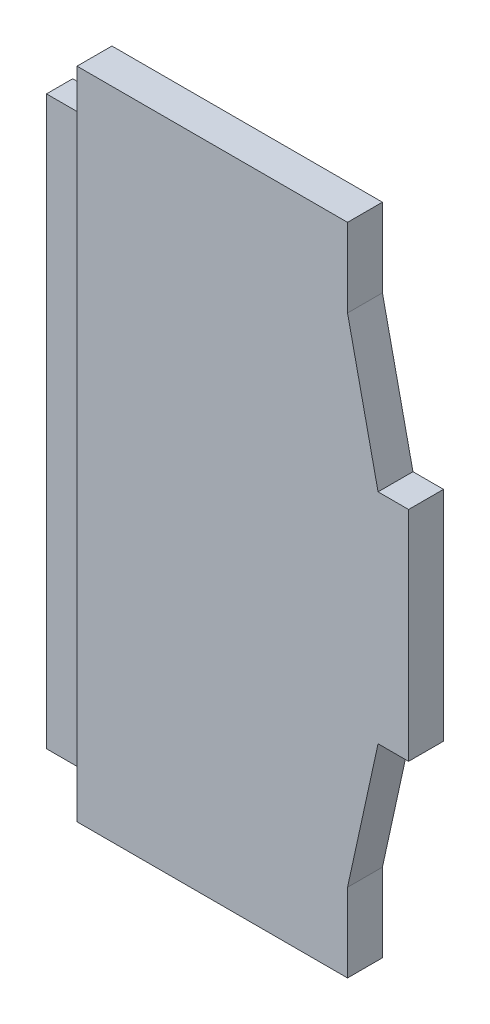
SolidWorks part; units mm, degrees
ref_plane "Front Plane" through (0, 0, 0) normal (0, 0, 1) x (1, 0, 0)
ref_plane "Top Plane" through (0, 0, 0) normal (0, 1, 0) x (1, 0, 0)
ref_plane "Right Plane" through (0, 0, 0) normal (1, 0, 0) x (0, 0, -1)
sketch "Sketch1" plane through (0, 0, 0) normal (0, 0, 1) x (1, 0, 0)
  line L0 (0, 37.5) -> (31, 37.5) construction
  line L1 (0, 0) -> (31, 0)
  line L2 (0, 0) -> (0, 75)
  line L3 (0, 75) -> (31, 75)
  line L4 (31, 0) -> (31, 9)
  line L5 (34.5, 50) -> (38, 50)
  line L6 (38, 50) -> (38, 25)
  line L7 (38, 25) -> (34.5, 25)
  line L8 (31, 66) -> (31, 75)
  line L9 (31, 50) -> (31, 37.5) construction
  line L10 (31, 37.5) -> (31, 25) construction
  line L11 (34.5, 50) -> (31, 66)
  line L12 (34.5, 25) -> (31, 9)
  line L13 (31, 25) -> (31, 9) construction
  line L14 (34.5, 25) -> (31, 25) construction
  line L15 (31, 50) -> (34.5, 50) construction
  line L16 (31, 50) -> (31, 66) construction
  line L17 (34, 45) -> (31, 45) construction
  line L18 (34, 45) -> (34, 50) construction
  circle A0 centre (34, 45) radius 1.55 construction
  circle A2 centre (34, 30) radius 1.55 construction
  dimension "D5" = 3.1
  dimension "D1" = 31
  dimension "D2" = 75
  dimension "D3" = 25
  dimension "D4" = 7
  dimension "D6" = 3
  dimension "D7" = 15
  dimension "D8" = 9
extrude "Boss-Extrude1" add sketch "Sketch1" along normal blind 4
sketch "Sketch3" plane through (0, 0, 0) normal (-1, 0, 0) x (0, 0, 1)
  line L0 (2, 0) -> (2, 75) construction
  line L1 (4, 0) -> (0, 0) construction
  line L2 (4, 75) -> (0, 75) construction
  line L3 (0, 37.5) -> (4, 37.5) construction
  line L4 (0.5, 70) -> (3.5, 70)
  line L5 (0.5, 70) -> (0.5, 5)
  line L6 (0.5, 5) -> (3.5, 5)
  line L7 (3.5, 70) -> (3.5, 5)
  line L8 (0, 75) -> (0, 0) construction
  line L9 (4, 75) -> (4, 0) construction
  dimension "D1" = 65
  dimension "D2" = 3
extrude "Boss-Extrude2" add sketch "Sketch3" along normal blind 4
